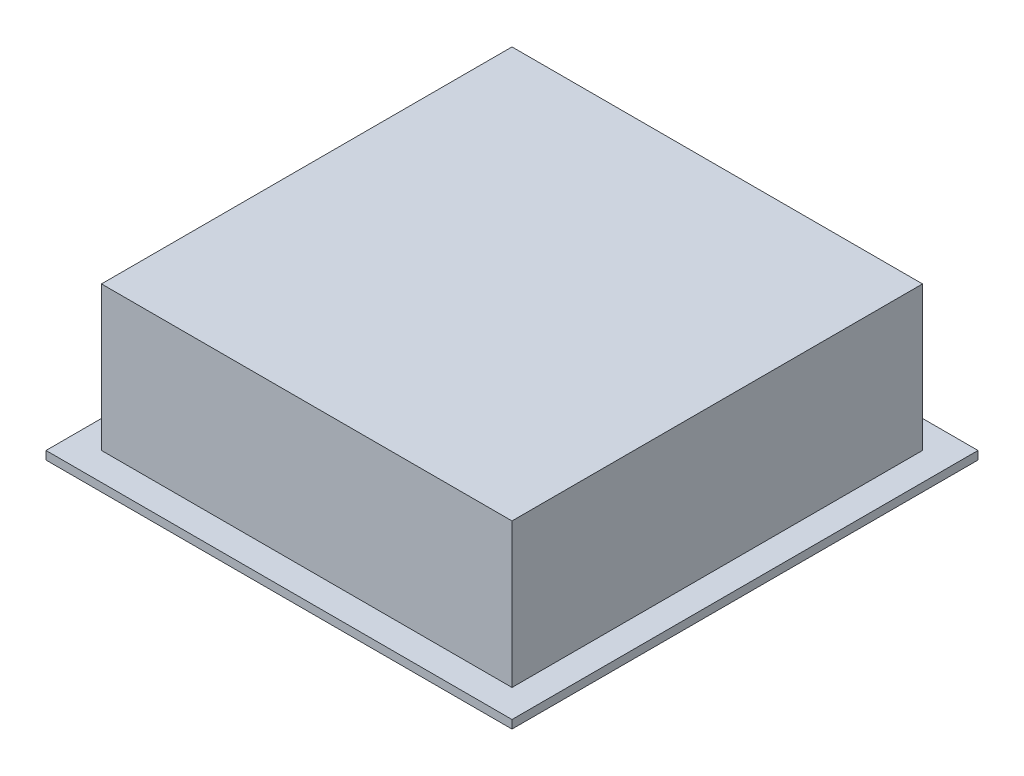
SolidWorks part; units mm, degrees
ref_plane "前视基准面" through (0, 0, 0) normal (0, 0, 1) x (1, 0, 0)
ref_plane "上视基准面" through (0, 0, 0) normal (0, 1, 0) x (1, 0, 0)
ref_plane "右视基准面" through (0, 0, 0) normal (1, 0, 0) x (0, 0, -1)
sketch "草图1" plane through (0, 0, 0) normal (0, 1, 0) x (1, 0, 0)
  line L1 (-40.1772, 31.8228) -> (43.8228, 31.8228)
  line L2 (-40.1772, 31.8228) -> (-40.1772, -52.1772)
  line L3 (-40.1772, -52.1772) -> (43.8228, -52.1772)
  line L4 (43.8228, 31.8228) -> (43.8228, -52.1772)
  dimension "D1" = 84
  dimension "D2" = 84
extrude "凸台-拉伸1" add sketch "草图1" along normal blind 1.5
sketch "草图2" plane through (0, 1.5, 0) normal (0, 1, 0) x (1, 0, 0)
  line L0 (43.8228, 31.8228) -> (-40.1772, 31.8228) construction
  line L1 (-35.1772, 26.8228) -> (38.8228, 26.8228)
  line L2 (-35.1772, 26.8228) -> (-35.1772, -47.1772)
  line L3 (-35.1772, -47.1772) -> (38.8228, -47.1772)
  line L4 (38.8228, 26.8228) -> (38.8228, -47.1772)
  line L5 (-40.1772, 31.8228) -> (-40.1772, -52.1772) construction
  line L6 (43.8228, -52.1772) -> (43.8228, 31.8228) construction
  line L7 (-40.1772, -52.1772) -> (43.8228, -52.1772) construction
  dimension "D1" = 5
  dimension "D2" = 5
  dimension "D3" = 5
  dimension "D4" = 5
extrude "凸台-拉伸2" add sketch "草图2" along normal blind 26
sketch "草图3" plane through (0, 0, 0) normal (0, -1, 0) x (1, 0, 0)
  line L0 (-40.1772, -31.8228) -> (-40.1772, 52.1772) construction
  line L1 (-35.1772, 47.1772) -> (38.8228, 47.1772)
  line L2 (-35.1772, 47.1772) -> (-35.1772, -26.8228)
  line L3 (-35.1772, -26.8228) -> (38.8228, -26.8228)
  line L4 (38.8228, 47.1772) -> (38.8228, -26.8228)
  line L5 (-40.1772, 52.1772) -> (43.8228, 52.1772) construction
  line L6 (43.8228, 52.1772) -> (43.8228, -31.8228) construction
  line L7 (43.8228, -31.8228) -> (-40.1772, -31.8228) construction
  dimension "D1" = 5
  dimension "D2" = 5
  dimension "D3" = 5
  dimension "D4" = 5
extrude "凸台-拉伸3" add sketch "草图3" along normal blind 1
